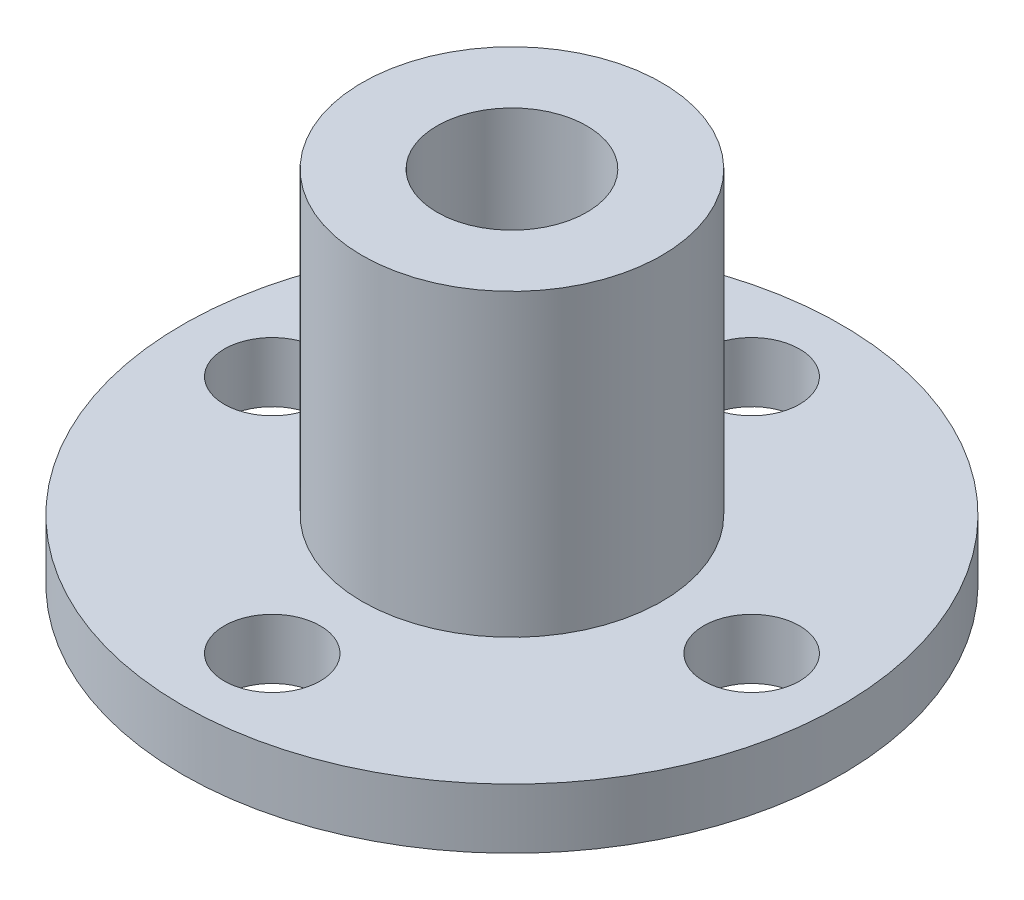
SolidWorks part; units mm, degrees
ref_plane "Front Plane" through (0, 0, 0) normal (0, 0, 1) x (1, 0, 0)
ref_plane "Top Plane" through (0, 0, 0) normal (0, 1, 0) x (1, 0, 0)
ref_plane "Right Plane" through (0, 0, 0) normal (1, 0, 0) x (0, 0, -1)
sketch "Sketch1" plane through (0, 0, 0) normal (0, 1, 0) x (1, 0, 0)
  circle A0 centre (0, 0) radius 11
  dimension "D1" = 22
extrude "Boss-Extrude1" add sketch "Sketch1" along normal blind 2
sketch "Sketch3" plane through (0, 2, 0) normal (0, 1, 0) x (1, 0, 0)
  circle A0 centre (0, 0) radius 5
  dimension "D1" = 10
extrude "Boss-Extrude2" add sketch "Sketch3" along normal blind 10
sketch "Sketch4" plane through (0, 12, 0) normal (0, 1, 0) x (1, 0, 0)
  circle A0 centre (0, 0) radius 2.5
  dimension "D1" = 5
extrude "Cut-Extrude1" cut sketch "Sketch4" against normal through all
sketch "Sketch5" plane through (0, 0, 0) normal (0, -1, 0) x (1, 0, 0)
  line L0 (0, 0) -> (15.3133, 0) construction
  line L1 (0, 0) -> (0, -1.7451) construction
  circle A0 centre (0, 8) radius 1.6
  circle A1 centre (-8, 0) radius 1.6
  circle A2 centre (0, -8) radius 1.6
  circle A3 centre (8, 0) radius 1.6
  point P12 (0, 0)
  point P15 (0, 0)
  point P16 (0, 0)
  point P17 (0, 0)
  point P18 (0, 0)
  dimension "D1" = 3.2
  dimension "D2" = 8
  dimension "D3" = 8
  dimension "D4" = 8
  dimension "D5" = 8
extrude "Cut-Extrude2" cut sketch "Sketch5" against normal through all
